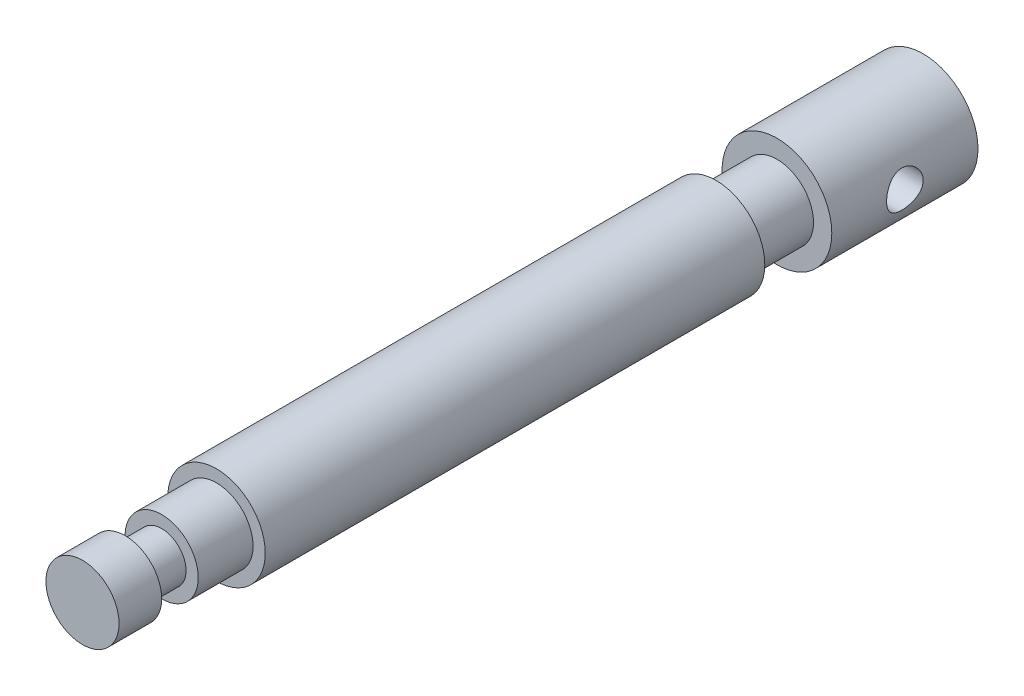
SolidWorks part; units mm, degrees
material "AISI 1045 Steel, cold drawn"
ref_plane "Front Plane" through (0, 0, 0) normal (0, 0, 1) x (1, 0, 0)
ref_plane "Top Plane" through (0, 0, 0) normal (0, 1, 0) x (1, 0, 0)
ref_plane "Right Plane" through (0, 0, 0) normal (1, 0, 0) x (0, 0, -1)
sketch "Sketch1" plane through (0, 0, 0) normal (1, 0, 0) x (0, 0, -1)
  line L0 (-78.3499, 0) -> (78.3499, 0) construction
  line L1 (-48.2008, 8) -> (33.7992, 8)
  line L2 (-48.2008, 8) -> (-48.2008, 6)
  line L3 (-48.2008, 6) -> (-57.2008, 6)
  line L4 (-57.2008, 6) -> (-57.2008, 4)
  line L5 (-57.2008, 4) -> (-63.2008, 4)
  line L6 (-63.2008, 4) -> (-63.2008, 6)
  line L7 (-63.2008, 6) -> (-70.2008, 6)
  line L8 (-70.2008, 6) -> (-70.2008, 0)
  line L9 (33.7992, 8) -> (33.7992, 6)
  line L10 (33.7992, 6) -> (43.7992, 6)
  line L11 (43.7992, 6) -> (43.7992, 9)
  line L12 (43.7992, 9) -> (67.7992, 9)
  line L13 (67.7992, 9) -> (67.7992, 0)
  line L14 (-70.2008, 0) -> (67.7992, 0)
  point P4 (0, 0)
  point P8 (-7.2008, 8)
  dimension "D1" = 82
  dimension "D2" = 9
  dimension "D3" = 24
  dimension "D4" = 12
  dimension "D5" = 16
  dimension "D6" = 12
  dimension "D7" = 8
  dimension "D8" = 12
  dimension "D9" = 7
  dimension "D10" = 6
  dimension "D11" = 138
  dimension "D12" = 10
revolve "Revolve1" add sketch "Sketch1" angle 360 about L0
sketch "Sketch2" plane through (0, 0, 0) normal (1, 0, 0) x (0, 0, -1)
  line L0 (43.7992, -9) -> (67.7992, -9) construction
  line L1 (67.7992, -9) -> (67.7992, 9) construction
  circle A0 centre (55.7992, 0) radius 3
  dimension "D1" = 6
  dimension "D2" = 9
  dimension "D3" = 12
extrude "Cut-Extrude1" cut sketch "Sketch2" against normal through all both and the other way through all contours A0
